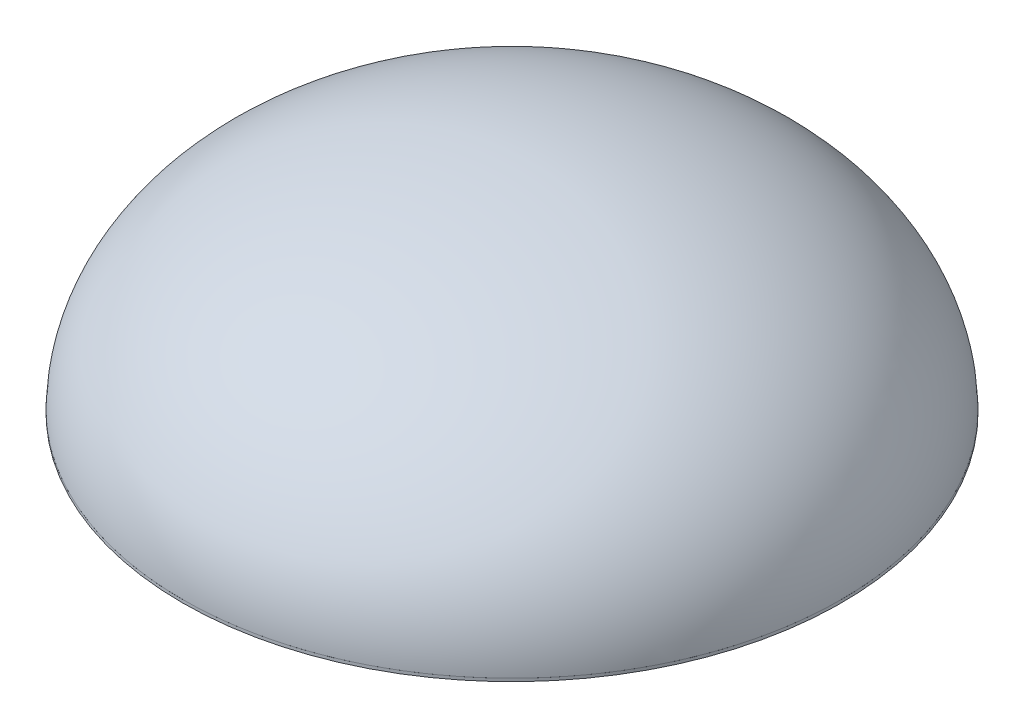
SolidWorks part; units mm, degrees
material "ASTM A36 Steel"
ref_plane "Front Plane" through (0, 0, 0) normal (0, 0, 1) x (1, 0, 0)
ref_plane "Top Plane" through (0, 0, 0) normal (0, 1, 0) x (1, 0, 0)
ref_plane "Right Plane" through (0, 0, 0) normal (1, 0, 0) x (0, 0, -1)
sketch "Sketch1" plane through (0, 0, 0) normal (0, 1, 0) x (1, 0, 0)
  circle A0 centre (0, 0) radius 109.55
  dimension "D1" = 219.1
extrude "Extrude-Thin1" add sketch "Sketch1" along normal blind 1 thin thin type one direction reverse wall 8.2
sketch "Sketch3" plane through (0, 0, 0) normal (1, 0, 0) x (0, 0, -1)
  line L1 (0, 0) -> (109.55, 0) construction
  line L2 (0, 0) -> (0, 71.6) construction
  line L3 (0, 71.6) -> (109.55, 71.6) construction
  line L4 (109.55, 0) -> (109.55, 71.6) construction
  line L6 (0, 63.4) -> (0, 71.6)
  line L7 (101.35, 0) -> (109.55, 0)
  ellipse E0 centre (0, 0) end of major axis (109.55, 0) minor radius 71.6 (109.55, 0) -> (0, 71.6) ccw
  spline S0 degree 1 poles (101.35, 0) (0, 63.4) knots 0 0 1 1 construction
  spline S1 degree 3 poles (101.35, 0) (101.35, 1.9375) (101.06, 5.7956) (99.3122, 13.5161) (94.8945, 23.0922) (85.9353, 34.0939) (73.486, 44.0334) (57.985, 52.3616) (40.06, 58.6314) (23.7235, 61.8726) (10.2308, 63.1809) (3.4054, 63.4) (0, 63.4) knots 0 0 0 0 0.098175 0.19635 0.392699 0.589049 0.785398 0.981748 1.178097 1.374447 1.472622 1.570796 1.570796 1.570796 1.570796
  point P4 (0, 0)
  point P5 (0, 0)
  point P7 (0, 0)
  point P8 (0, 0)
  dimension "D1" = 8.2
  dimension "D3" = 8.2
  dimension "D4" = 101.35
  dimension "D5" = 71.6
  dimension "D2" = 8.2
revolve "Revolve1" add sketch "Sketch3" angle 360 about L2
